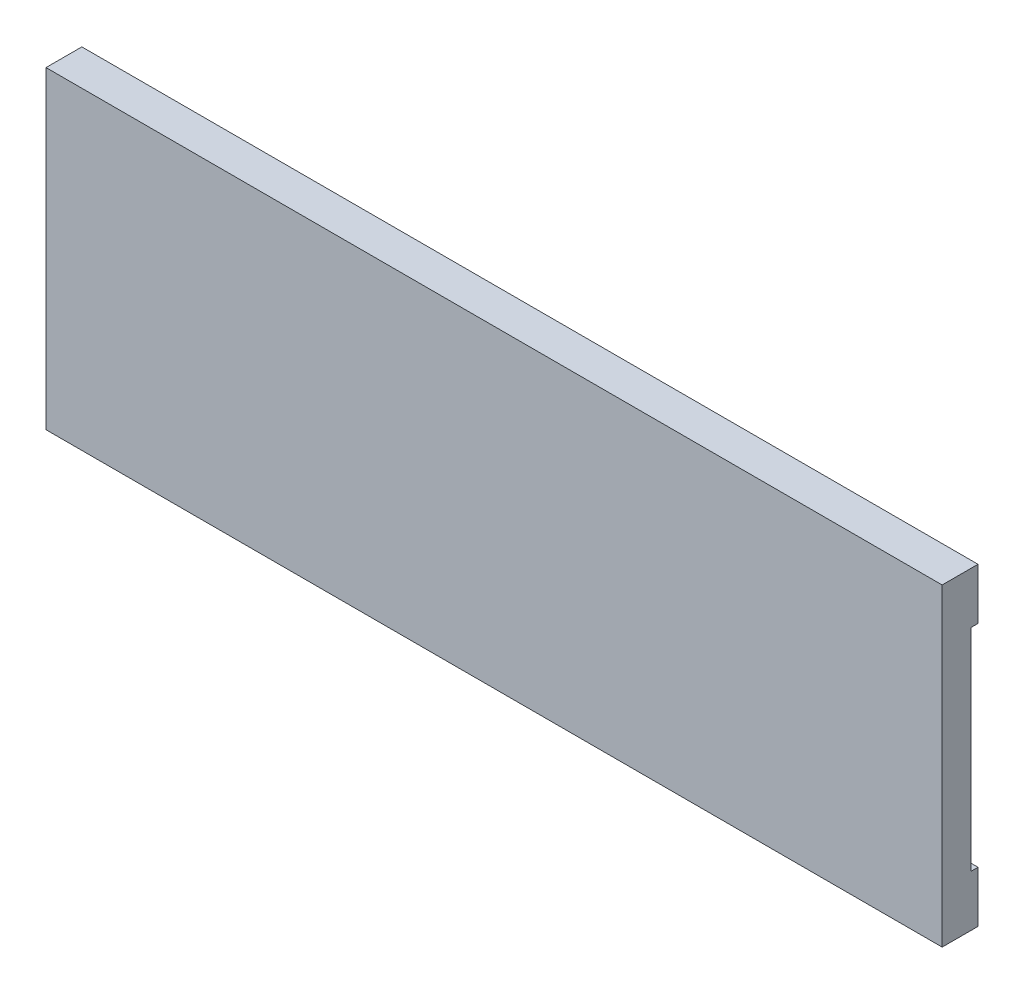
SolidWorks part; units mm, degrees
ref_plane "Front Plane" through (0, 0, 0) normal (0, 0, 1) x (1, 0, 0)
ref_plane "Top Plane" through (0, 0, 0) normal (0, 1, 0) x (1, 0, 0)
ref_plane "Right Plane" through (0, 0, 0) normal (1, 0, 0) x (0, 0, -1)
sketch "Sketch1" plane through (0, 0, 0) normal (0, 0, 1) x (1, 0, 0)
  line L1 (-63.5, 22.225) -> (63.5, 22.225)
  line L2 (-63.5, 22.225) -> (-63.5, -22.225)
  line L3 (-63.5, -22.225) -> (63.5, -22.225)
  line L4 (63.5, 22.225) -> (63.5, -22.225)
  line L5 (-63.5, 22.225) -> (63.5, -22.225) construction
  line L6 (-63.5, -22.225) -> (63.5, 22.225) construction
  point P0 (0, 0)
  dimension "D1" = 127
  dimension "D2" = 44.45
extrude "Boss-Extrude1" add sketch "Sketch1" along normal blind 5.08
sketch "Sketch2" plane through (0, 0, 0) normal (0, 0, -1) x (-1, 0, 0)
  line L2 (29.1071, 14.4526) -> (-4.4746, 14.4526)
  line L3 (-4.4746, -14.4526) -> (29.1071, -14.4526)
  line L4 (29.1071, 14.4526) -> (-4.4746, 14.4526)
  line L5 (-4.4746, -14.4526) -> (29.1071, -14.4526)
  arc A6 (34.826, 10.8623) -> (29.1071, 14.4526) centre (29.1071, 8.1026) ccw
  arc A7 (-4.4746, 14.4526) -> (-10.1935, 10.8623) centre (-4.4746, 8.1026) ccw
  arc A8 (-10.1935, 10.8623) -> (-10.1935, -10.8623) centre (12.3163, 0) ccw
  arc A9 (-10.1935, -10.8623) -> (-4.4746, -14.4526) centre (-4.4746, -8.1026) ccw
  arc A10 (29.1071, -14.4526) -> (34.826, -10.8623) centre (29.1071, -8.1026) ccw
  arc A11 (34.826, -10.8623) -> (34.826, 10.8623) centre (12.3163, 0) ccw
  arc A12 (34.826, 10.8623) -> (29.1071, 14.4526) centre (29.1071, 8.1026) ccw
  arc A13 (-4.4746, 14.4526) -> (-10.1935, 10.8623) centre (-4.4746, 8.1026) ccw
  arc A14 (-10.1935, 10.8623) -> (-10.1935, -10.8623) centre (12.3163, 0) ccw
  arc A15 (-10.1935, -10.8623) -> (-4.4746, -14.4526) centre (-4.4746, -8.1026) ccw
  arc A16 (29.1071, -14.4526) -> (34.826, -10.8623) centre (29.1071, -8.1026) ccw
  arc A17 (34.826, -10.8623) -> (34.826, 10.8623) centre (12.3163, 0) ccw
  dimension "D1" = 0
sketch "Sketch3" plane through (0, 0, 0) normal (0, 0, -1) x (-1, 0, 0)
  line L0 (-63.5, 14.9606) -> (-34.3655, 14.9606)
  line L2 (-25.908, 14.9606) -> (-25.908, -14.9606) construction
  line L3 (-34.3655, -14.9606) -> (-63.5, -14.9606)
  line L5 (-63.5, -14.9606) -> (-63.5, 14.9606)
  line L6 (-63.5, -22.225) -> (-63.5, 22.225) construction
  line L7 (29.1071, 14.4526) -> (-4.4746, 14.4526) construction
  line L8 (-4.4746, -14.4526) -> (29.1071, -14.4526) construction
  arc A0 (-28.7334, 11.5434) -> (-28.7334, -11.5434) centre (-50.9016, 0) cw
  arc A1 (34.826, -10.8623) -> (34.826, 10.8623) centre (12.3163, 0) ccw construction
  arc A2 (-28.7334, -11.5434) -> (-34.3655, -14.9606) centre (-34.3655, -8.6106) cw
  arc A3 (-28.7334, 11.5434) -> (-34.3655, 14.9606) centre (-34.3655, 8.6106) ccw
  arc A4 (29.1071, -14.4526) -> (34.826, -10.8623) centre (29.1071, -8.1026) ccw construction
  point P2 (0, 0)
  point P19 (-30.8801, -14.9606)
  point P22 (-30.8801, 14.9606)
  dimension "D1" = 37.592
  dimension "D2" = 0.508
  dimension "D3" = 0.508
extrude "Cut-Extrude1" cut sketch "Sketch3" against normal blind 0.9652
sketch "Sketch5" plane through (0, 0, 0) normal (0, 0, -1) x (-1, 0, 0)
  line L0 (-25.908, 0) -> (-25.908, -24.878)
  arc A0 (-28.7334, -11.5434) -> (-28.7334, 11.5434) centre (-50.9016, 0) ccw construction
ref_plane "Plane1" through (25.908, 0, 0) normal (1, 0, 0) x (0, 0, -1)
